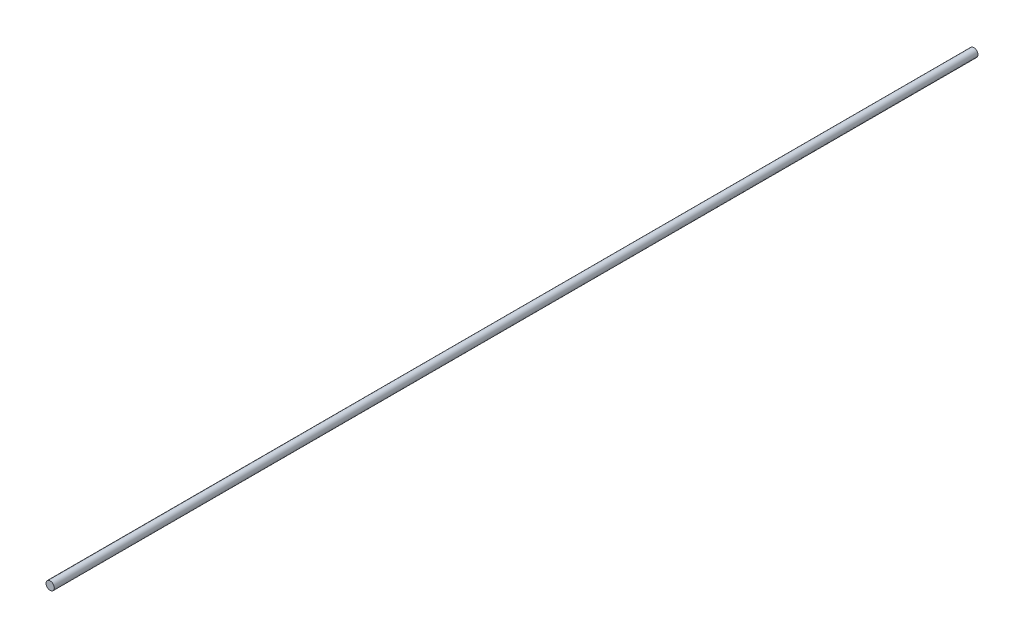
SolidWorks part; units mm, degrees
ref_plane "Front Plane" through (0, 0, 0) normal (0, 0, 1) x (1, 0, 0)
ref_plane "Top Plane" through (0, 0, 0) normal (0, 1, 0) x (1, 0, 0)
ref_plane "Right Plane" through (0, 0, 0) normal (1, 0, 0) x (0, 0, -1)
sketch "Esquisse1" plane through (0, 0, 0) normal (0, 0, 1) x (1, 0, 0)
  circle A0 centre (0, 0) radius 3.1
extrude "Boss.-Extru.1" add sketch "Esquisse1" along normal blind 690
